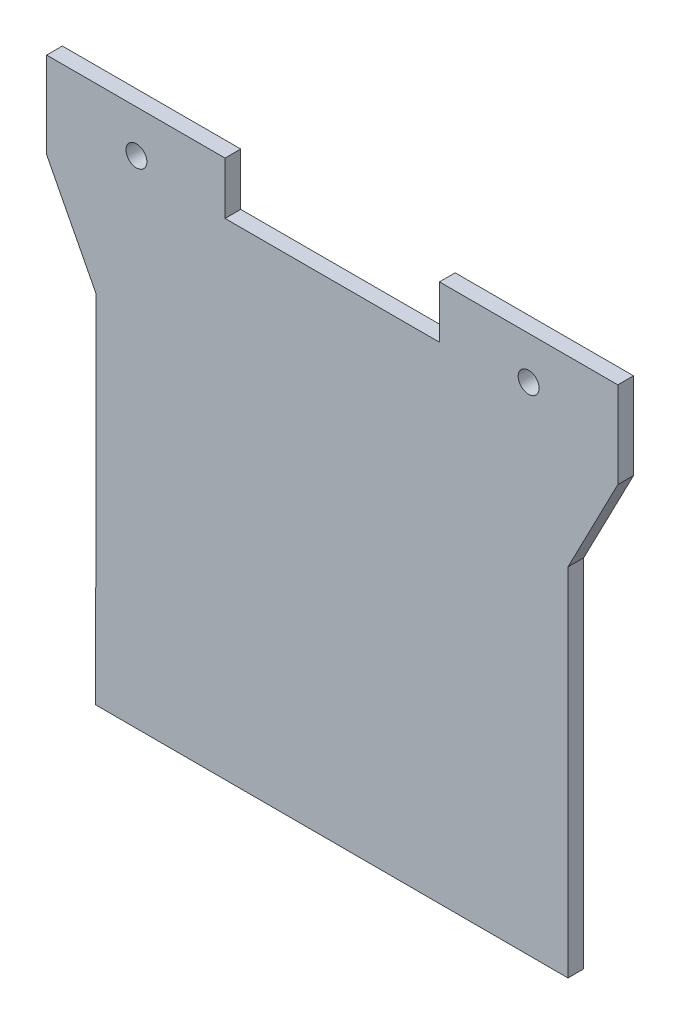
SolidWorks part; units mm, degrees
ref_plane "Front Plane" through (0, 0, 0) normal (0, 0, 1) x (1, 0, 0)
ref_plane "Top Plane" through (0, 0, 0) normal (0, 1, 0) x (1, 0, 0)
ref_plane "Right Plane" through (0, 0, 0) normal (1, 0, 0) x (0, 0, -1)
sketch "Sketch1" plane through (0, 0, 0) normal (0, 0, 1) x (1, 0, 0)
  line L0 (-17.1711, 8.1021) -> (16.943, 8.1021)
  line L1 (92.0524, 8.1021) -> (92.0524, -8.4362)
  line L2 (92.0524, -8.4362) -> (82.5304, -26.8121)
  line L3 (82.5304, -26.8121) -> (82.5304, -94.8962)
  line L4 (-7.811, -94.8251) -> (82.5304, -94.8962)
  line L5 (37.4328, -1.8979) -> (37.362, -91.9633) construction
  line L6 (-17.197, -8.3503) -> (-17.1711, 8.1021)
  line L7 (-17.197, -8.3503) -> (-7.7039, -26.7411)
  line L8 (-7.811, -94.8251) -> (-7.7039, -26.7411)
  line L10 (57.9476, 8.1021) -> (92.0524, 8.1021)
  line L11 (16.943, -1.8979) -> (57.9476, -1.8979)
  line L12 (16.943, -1.8979) -> (16.943, 8.1021)
  line L14 (57.9476, -1.8979) -> (57.9476, 8.1021)
  circle A0 centre (0, 0) radius 2
  circle A1 centre (75, 0) radius 2
  point P9 (75, 8.1021)
  dimension "D1" = 75
  dimension "D2" = 4
  dimension "D3" = 10
extrude "Boss-Extrude1" add sketch "Sketch1" along normal blind 3
